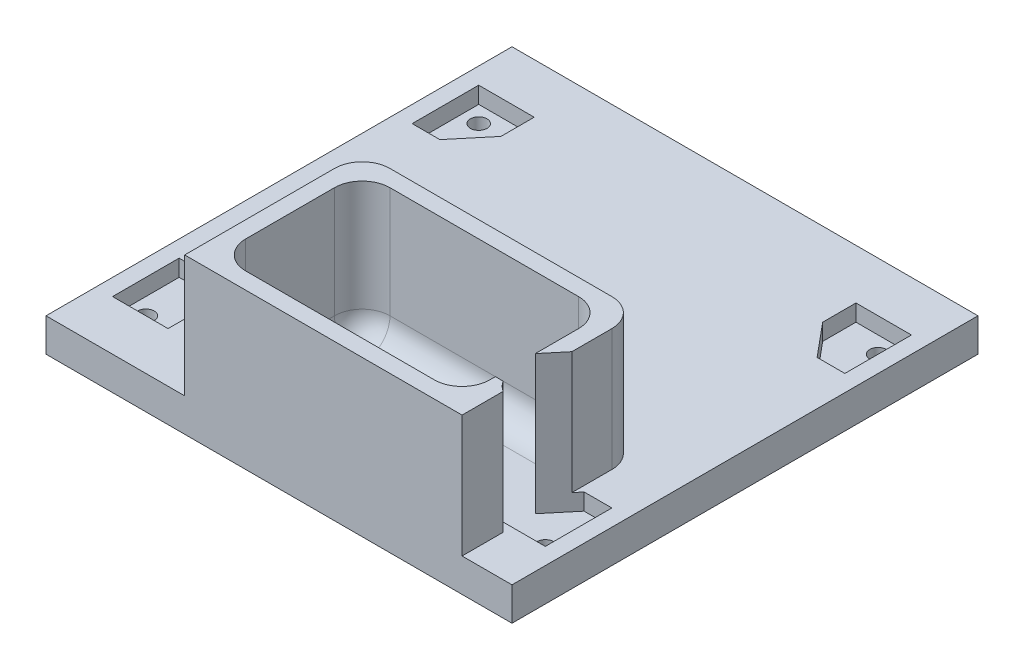
SolidWorks part; units mm, degrees
other "Markup1"
sketch "Sketch7"
sketch "Sketch12" plane through (84, 28, 0) normal (0.1424, 0.9893, 0.0306) x (0.9898, -0.1423, -0.003)
sketch "Sketch14" plane through (84, 28, 0) normal (0.1424, 0.9893, 0.0306) x (0.9898, -0.1423, -0.003)
sketch "Sketch15" plane through (84, 28, 0) normal (0.1424, 0.9893, 0.0306) x (0.9898, -0.1423, -0.003)
material "PVB"
ref_plane "Front Plane" through (0, 0, 0) normal (0, 0, 1) x (1, 0, 0)
ref_plane "Top Plane" through (0, 0, 0) normal (0, 1, 0) x (1, 0, 0)
ref_plane "Right Plane" through (0, 0, 0) normal (1, 0, 0) x (0, 0, -1)
sketch "Sketch1" plane through (0, 0, 0) normal (0, 1, 0) x (1, 0, 0)
  line L1 (0, 0) -> (84, 0)
  line L2 (0, 0) -> (0, 84)
  line L3 (0, 84) -> (84, 84)
  line L4 (84, 0) -> (84, 84)
  dimension "D1" = 84
  dimension "D2" = 84
extrude "Boss-Extrude1" add sketch "Sketch1" along normal blind 6
sketch "Sketch2" plane through (0, 6, 0) normal (0, 1, 0) x (1, 0, 0)
  line L0 (84, 84) -> (0, 84) construction
  line L1 (0, 84) -> (0, 0) construction
  line L2 (0, 0) -> (84, 0) construction
  line L3 (84, 0) -> (84, 84) construction
  circle A0 centre (6, 72) radius 1.5
  circle A1 centre (6, 12) radius 1.5
  circle A2 centre (78, 12) radius 1.5
  circle A3 centre (78, 72) radius 1.5
  dimension "D1" = 3
  dimension "D2" = 3
  dimension "D3" = 3
  dimension "D4" = 3
  dimension "D6" = 6
  dimension "D7" = 12
  dimension "D8" = 6
  dimension "D9" = 6
  dimension "D10" = 12
  dimension "D11" = 6
  dimension "D5" = 12
  dimension "D12" = 12
extrude "Cut-Extrude1" cut sketch "Sketch2" against normal through all
ref_plane "Plane1" through (0, 0, -42) normal (0, 0, 1) x (1, 0, 0)
sketch "Sketch4" plane through (0, 6, 0) normal (0, 1, 0) x (1, 0, 0)
  line L0 (3, 21) -> (3, 9)
  line L1 (3, 9) -> (13, 9)
  line L2 (13, 15) -> (8, 21)
  line L3 (3, 21) -> (8, 21)
  line L4 (8, 21) -> (13, 15)
  line L5 (13, 15) -> (13, 9)
  line L6 (0, 84) -> (0, 0) construction
  line L7 (0, 0) -> (84, 0) construction
  circle A0 centre (6, 12) radius 1.5
  circle A1 centre (6, 12) radius 1.5 construction
  circle M21 centre (6, 12) radius 1.5
  dimension "D1" = 3
  dimension "D2" = 9
  dimension "D3" = 12
  dimension "D4" = 10
  dimension "D5" = 6
  dimension "D6" = 5
extrude "Cut-Extrude4" cut sketch "Sketch4" against normal blind 3 contours L5 L2 L3 L0 L1 M21
mirror "Mirror2" about plane through (0, 0, -42) normal (0, 0, 1) of "Cut-Extrude4"
ref_plane "Plane2" through (42, 0, 0) normal (-1, 0, 0) x (0, 0, 1)
mirror "Mirror3" about plane through (42, 0, 0) normal (-1, 0, 0) of "Mirror2", "Cut-Extrude4"
sketch "Sketch5" plane through (0, 6, 0) normal (0, 1, 0) x (1, 0, 0)
  line L0 (25, 32) -> (25, 0)
  line L1 (25, 32) -> (75, 32)
  line L2 (25, 0) -> (75, 0)
  line L3 (75, 32) -> (75, 0)
  line L4 (25, 32) -> (75, 0) construction
  line L5 (25, 0) -> (75, 32) construction
  line L7 (42, 3.3) -> (42, -3.3) construction
  line L12 (0, 0) -> (84, 0) construction
  point P1 (50, 16)
  dimension "D1" = 50
  dimension "D2" = 32
  dimension "D3" = 8
extrude "Boss-Extrude2" add sketch "Sketch5" along normal blind 22
sketch "Sketch6" plane through (0, 28, 0) normal (0, 1, 0) x (1, 0, 0)
  line L14 (72, 29) -> (28, 29)
  line L15 (28, 29) -> (28, 3)
  line L16 (28, 3) -> (72, 3)
  line L17 (72, 3) -> (72, 29)
  line L18 (72, 29) -> (28, 29)
  line L19 (28, 29) -> (28, 3)
  line L20 (28, 3) -> (72, 3)
  line L21 (72, 3) -> (72, 29)
  dimension "D1" = 3
extrude "Cut-Extrude5" cut sketch "Sketch6" against normal blind 25
sketch "Sketch8" plane through (0, 28, 0) normal (0, 1, 0) x (1, 0, 0)
  line L0 (81, 21) -> (81, 9) construction
  line L1 (81, 9) -> (72, 9) construction
  line L2 (72, 16.2) -> (76, 21) construction
  line L3 (81, 21) -> (76, 21) construction
  line L4 (75, 32) -> (25, 32)
  line L5 (25, 32) -> (25, 0)
  line L6 (25, 0) -> (75, 0)
  line L7 (75, 0) -> (75, 32)
  line L8 (75, 32) -> (25, 32)
  line L9 (25, 32) -> (25, 0)
  line L10 (25, 0) -> (75, 0)
  line L11 (75, 0) -> (75, 32)
  line L12 (81, 21) -> (81, 9)
  line L13 (81, 9) -> (72, 9)
  line L14 (72, 16.2) -> (76, 21)
  line L15 (81, 21) -> (76, 21)
  line L16 (72, 16.2) -> (72, 9)
  circle A0 centre (78, 12) radius 1.5 construction
  circle A1 centre (78, 12) radius 1.5
  circle A2 centre (78, 12) radius 5.5
  line M17 (72, 29) -> (72, 3)
  dimension "D2" = 11
  dimension "D1" = 0
extrude "Cut-Extrude14" cut sketch "Sketch8" against normal up to surface (22 mm away) contours L11 A2 L13 M17 | L13 A2 L11
sketch "Sketch13" plane through (0, 3, 0) normal (0, 1, 0) x (1, 0, 0)
  line L5 (28, 29) -> (28, 3)
  line L6 (72, 9) -> (81, 9)
  line L7 (81, 9) -> (81, 21)
  line L8 (81, 21) -> (76, 21)
  line L9 (76, 21) -> (72, 16.2)
  line L11 (72, 9) -> (81, 9)
  line L12 (81, 9) -> (81, 21)
  line L13 (81, 21) -> (76, 21)
  line L14 (76, 21) -> (72, 16.2)
  line L19 (28, 29) -> (28, 3)
  line L20 (72, 29) -> (28, 29)
  line L22 (72, 3) -> (72, 9)
  line L23 (72, 3) -> (72, 9)
  line L24 (72, 16.2) -> (72, 29)
  line L25 (72, 16.2) -> (72, 29)
  line L26 (72, 29) -> (28, 29)
  line L28 (28, 3) -> (72, 3)
  line L29 (28, 3) -> (72, 3)
  dimension "D1" = 0
extrude "Cut-Extrude15" cut sketch "Sketch13" along normal through all
fillet "Fillet2" radius 5 2 edges at (25, 17, -32) (75, 17, -32)
fillet "Fillet3" radius 5 7 edges at (72, 15.5, -29) (50, 3, -3) (72, 15.5, -3) (28, 3, -16) (28, 15.5, -3) (50, 3, -29) (28, 15.5, -29)
